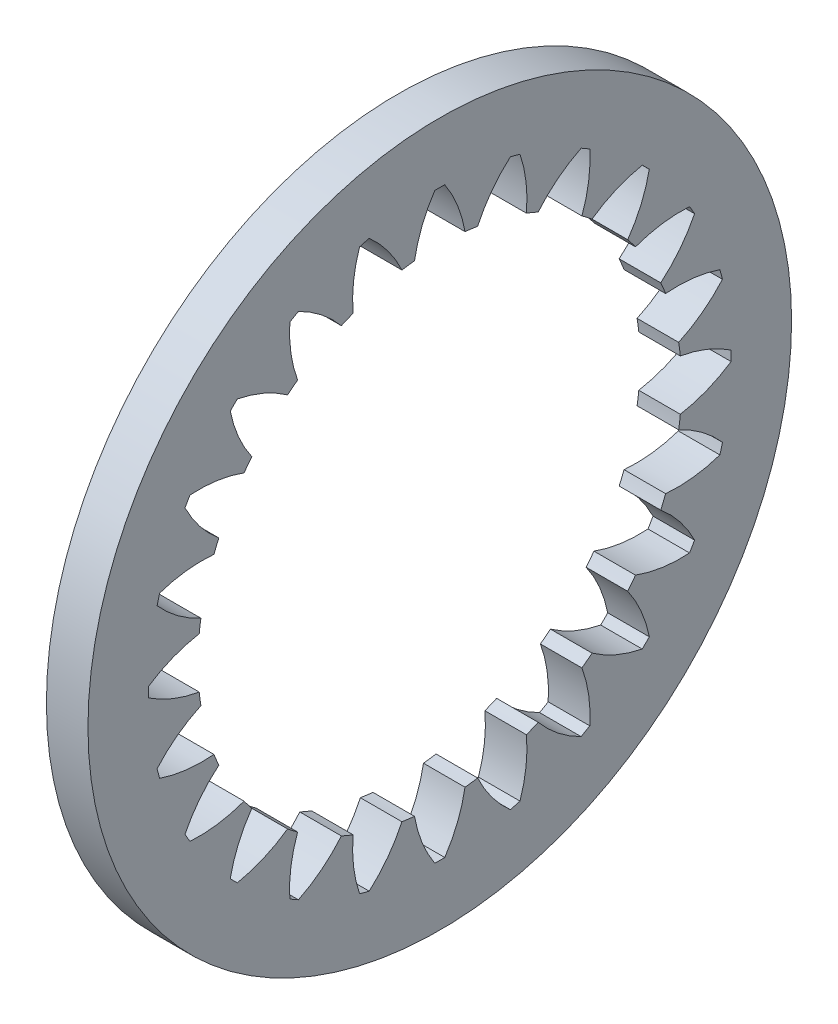
SolidWorks part; units mm, degrees
ref_plane "Plane1" through (0, 0, 0) normal (0, 0, 1) x (1, 0, 0)
ref_plane "Plane2" through (0, 0, 0) normal (0, 1, 0) x (1, 0, 0)
ref_plane "Plane3" through (0, 0, 0) normal (1, 0, 0) x (0, 0, -1)
other "Configuration Table"
sketch "HoldingSke" plane through (0, 0, 0) normal (0, 1, 0) x (1, 0, 0)
  line L0 (0, 0) -> (-0.0273, -0.1551)
  line L1 (-15, 0) -> (100, 0) construction
  line L2 (0, 0) -> (-2.1039, 2.3779)
  line L3 (0, 0) -> (-11.863, 4.5341)
  line L4 (0, 0) -> (7.8894, 3.5126)
  line L5 (0, 0) -> (-23.7986, -8.8762)
  line L6 (0, 0) -> (-10.5278, -7.1032)
  line L7 (-2.1039, 2.3779) -> (3.3635, 27.1825)
  line L8 (-76.2, 8.7279) -> (-54.61, 8.7279)
  line L9 (-67.7845, 28.3722) -> (-49.3413, 33.142)
  line L10 (-76.2, 71.12) -> (104.1128, 71.12)
  line L11 (0, 0) -> (-12, 0)
  line L12 (-76.2, 101.6) -> (-75.9714, 101.6)
  line L13 (24.9733, 27.94) -> (52.9518, 28.4284)
  line L14 (24.9733, 27.94) -> (24.9746, 27.94)
  line L15 (24.9733, 27.94) -> (100.4006, 29.5858)
  circle A0 centre (0, 0) radius 101.6
  circle A1 centre (0, 0) radius 12.7
  circle A2 centre (0, 0) radius 12.7
  dimension "MHD" = 25.4
  dimension "Hub_dia" = 25.4
  dimension "Diameter" = 203.2
  dimension "Num_teeth" = 24
  dimension "Pitch" = 0.1575
  dimension "Overall_len" = 25.4
  dimension "Show_teeth" = 100
  dimension "Thickness" = 12.7
  dimension "OAL" = 25.4001
  dimension "T_dim" = 21.59
  dimension "Ap" = 14.5
  dimension "H" = 19.05
  dimension "Pitch_radius" = 180.3128
  dimension "Width" = 12
  dimension "Backlash" = 0.2286
  dimension "Addendum_fac" = 1
  dimension "Dedendum_fac" = 1.25
  dimension "Clearance_fac" = 0.25
  dimension "Dedendum_add" = 0.0013
  dimension "Module" = 6.35
sketch "BasProSke" plane through (0, 0, 0) normal (0, 1, 0) x (1, 0, 0)
  line L0 (-10, 0) -> (60, 0) construction
  line L1 (0, 69.85) -> (0, 101.6)
  line L2 (0, 69.85) -> (12, 69.85)
  line L3 (12, 69.85) -> (12, 101.6)
  line L4 (12, 101.6) -> (0, 101.6)
  dimension "Diameter" = 203.2
  dimension "Thickness" = 12
  dimension "Inside_diameter" = 139.7
revolve "Base-Revolve" add sketch "BasProSke" angle 360 about L0
sketch "TooCutSke" plane through (0, 0, 0) normal (1, 0, 0) x (0, 0, -1)
  line L3 (5.5552, 75.9972) -> (5.5552, 53.6633) construction
  line L4 (0, 0) -> (0, 59.563) construction
  line L5 (0, 0) -> (-8.9185, 67.7429) construction
  line L6 (-30.2541, 62.9855) -> (28.8527, 70.767) construction
  circle A0 centre (0, 0) radius 76.2 construction
  circle A1 centre (0, 0) radius 84.1388 construction
  circle A2 centre (0, 0) radius 66.3956 construction
  circle A3 centre (0, 0) radius 69.8246 construction
  arc A4 (7.2948, 69.4425) -> (1.4425, 84.1264) centre (-30.2541, 62.9855) ccw
  arc A5 (7.2948, 69.4425) -> (-7.2948, 69.4425) centre (0, 0) ccw
  arc A6 (1.4425, 84.1264) -> (-1.4425, 84.1264) centre (0, 0) ccw
  arc A7 (-1.4425, 84.1264) -> (-7.2948, 69.4425) centre (30.2541, 62.9855) ccw
  dimension "Pitch_dia" = 152.4
  dimension "Base_dia" = 132.7911
  dimension "Root_dia" = 168.2775
  dimension "Overcut_dia" = 139.6492
  dimension "Flank_rad" = 38.1
  dimension "Half_ang" = 7.5
  dimension "Half_CT" = 5.5552
extrude "ToothCut" cut sketch "TooCutSke" along normal through all
fillet "Breaks" [suppressed] radius 0.635
fillet "RootFillets" [suppressed] radius 1.5888
pattern_circular "TeethCuts" count 24 every 15 about axis through (-10, 0, 0) along (1, 0, 0) of "RootFillets", "Breaks", "ToothCut"
equation "' \"Module@HoldingSke\" = 6.35"
equation "' \"Num_teeth@HoldingSke\" = 24"
equation "' \"Ap@HoldingSke\" =  14.5"
equation "' \"Ap@HoldingSke\" = 14.5"
equation "' \"Width@HoldingSke\" = 12"
equation "' \"Diameter@HoldingSke\" = 8 * 25.4"
equation "' \"Show_teeth@HoldingSke\" = 100"
equation "' \"Backlash@HoldingSke\" = 0.009 * 25.4"
equation "' \"Addendum_fac@HoldingSke\" = 1.0"
equation "' \"Dedendum_fac@HoldingSke\" = 1.25"
equation "' \"Dedendum_add@HoldingSke\" = 0.00005 * 25.4"
equation "' \"Clearance_fac@HoldingSke\" = 0.25"
equation "\"Pitch@HoldingSke\" = 1 / \"Module@HoldingSke\" "
equation "\"Overcut_dia@TooCutSke\" = (\"Num_teeth@HoldingSke\" - 2 * \"Addendum_fac@HoldingSke\") / \"Pitch@HoldingSke\" - 0.002 * 25.4"
equation "\"Pitch_dia@TooCutSke\" = \"Num_teeth@HoldingSke\" / \"Pitch@HoldingSke\""
equation "\"Base_dia@TooCutSke\" = \"Num_teeth@HoldingSke\" / \"Pitch@HoldingSke\" * cos((\"Ap@HoldingSke\"  * 3.14159265 / 180)) * 0.90"
equation "\"Root_dia@TooCutSke\" = \"Num_teeth@HoldingSke\"  / \"Pitch@HoldingSke\" + 2 *  \"Dedendum_fac@HoldingSke\"/ \"Pitch@HoldingSke\" + \"Dedendum_add@HoldingSke\" * 2"
equation "\"Half_ang@TooCutSke\" = 180 / \"Num_teeth@HoldingSke\""
equation "\"Half_CT@TooCutSke\" = \"Num_teeth@HoldingSke\" / \"Pitch@HoldingSke\" * sin((3.14159265 / 2 / \"Num_teeth@HoldingSke\")) / 2 + 10 * \"Backlash@HoldingSke\" / 4"
equation "\"Flank_rad@TooCutSke\" = \"Num_teeth@HoldingSke\" / \"Pitch@HoldingSke\" / 4"
equation "\"Radius@RootFillets\"= \"Clearance_fac@HoldingSke\" / \"Pitch@HoldingSke\" + \"Dedendum_add@HoldingSke\""
equation "\"Break_rad@Breaks\" = 0.02 / \"Pitch@HoldingSke\" * 5"
equation "\"Num_teeth@TeethCuts\" = int( \"Show_teeth@HoldingSke\" ) + 1"
equation "\"Num_teeth@TeethCuts\" = ((sgn( \"Num_teeth@TeethCuts\" - \"Num_teeth@HoldingSke\" )-1)*( \"Num_teeth@TeethCuts\" - \"Num_teeth@HoldingSke\" ))/-2+ \"Num_teeth@HoldingSke\""
equation "\"Num_teeth@TeethCuts\" = ((sgn( \"Num_teeth@TeethCuts\" - 2.0)+1)*( \"Num_teeth@TeethCuts\" - 2.0))/2 +2.0"
equation "\"Angle@TeethCuts\" = 360.0 / \"Num_teeth@HoldingSke\""
equation "\"Diameter@BasProSke\" = \"Num_teeth@HoldingSke\"  / \"Pitch@HoldingSke\" + 2 *  \"Dedendum_fac@HoldingSke\"/ \"Pitch@HoldingSke\" + \"Dedendum_add@HoldingSke\" * 2 + 0.002 * 25.4"
equation "\"Diameter@BasProSke\" = ((sgn( \"Diameter@BasProSke\"  - \"Diameter@HoldingSke\" )+1)*( \"Diameter@BasProSke\"  - \"Diameter@HoldingSke\" ))/2 + \"Diameter@HoldingSke\""
equation "\"Inside_diameter@BasProSke\" =  (\"Num_teeth@HoldingSke\" - 2 * \"Addendum_fac@HoldingSke\") / \"Pitch@HoldingSke\" "
equation "\"Thickness@BasProSke\"  = \"Width@HoldingSke\""
